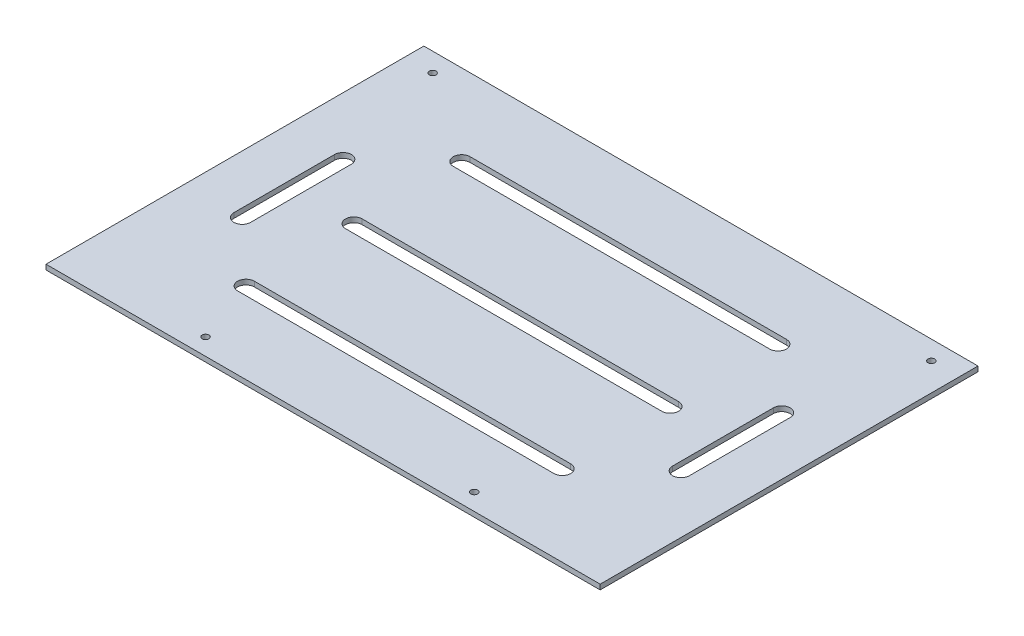
SolidWorks part; units mm, degrees
ref_plane "前视基准面" through (0, 0, 0) normal (0, 0, 1) x (1, 0, 0)
ref_plane "上视基准面" through (0, 0, 0) normal (0, 1, 0) x (1, 0, 0)
ref_plane "右视基准面" through (0, 0, 0) normal (1, 0, 0) x (0, 0, -1)
sketch "草图1" plane through (0, 0, 0) normal (0, 1, 0) x (1, 0, 0)
  line L1 (-145.5882, 128.3824) -> (184.4118, 128.3824)
  line L2 (-145.5882, 128.3824) -> (-145.5882, -96.6176)
  line L3 (-145.5882, -96.6176) -> (184.4118, -96.6176)
  line L4 (184.4118, 128.3824) -> (184.4118, -96.6176)
  dimension "D1" = 330
  dimension "D2" = 225
extrude "凸台-拉伸1" add sketch "草图1" along normal blind 3
sketch "草图2" plane through (0, 3, 0) normal (0, 1, 0) x (1, 0, 0)
  line L0 (-145.5882, 128.3824) -> (184.4118, -96.6176) construction
  line L1 (184.4118, 128.3824) -> (-145.5882, -96.6176) construction
sketch "草图3" plane through (0, 3, 0) normal (0, 1, 0) x (1, 0, 0)
  line L0 (-145.5882, 128.3824) -> (184.4118, -96.6176) construction
  line L1 (19.4118, 128.3824) -> (19.4118, -96.6176) construction
  line L2 (184.4118, 128.3824) -> (-145.5882, 128.3824) construction
  line L3 (-145.5882, -96.6176) -> (184.4118, -96.6176) construction
  line L5 (-145.5882, 15.8824) -> (184.4118, 15.8824) construction
  line L6 (-145.5882, 128.3824) -> (-145.5882, -96.6176) construction
  line L7 (184.4118, -96.6176) -> (184.4118, 128.3824) construction
  line L8 (19.4118, -86.6176) -> (50019.4118, -86.6176) construction
  circle A0 centre (-129.0637, 117.1156) radius 2
  circle A1 centre (167.8872, 117.1156) radius 2
  circle A2 centre (-60.5882, -86.6176) radius 2
  circle A3 centre (99.4118, -86.6176) radius 2
  dimension "D1" = 4
  dimension "D3" = 10
  dimension "D4" = 4
  dimension "D2" = 20
  dimension "D5" = 80
extrude "切除-拉伸1" cut sketch "草图3" against normal through all
sketch "草图4" plane through (0, 3, 0) normal (0, 1, 0) x (1, 0, 0)
  line L0 (-111.2352, 128.3824) -> (-111.2352, -96.6176) construction
  line L1 (184.4118, 128.3824) -> (-145.5882, 128.3824) construction
  line L2 (-145.5882, -96.6176) -> (184.4118, -96.6176) construction
  line L3 (19.4118, 128.3824) -> (19.4118, -96.6176) construction
  line L4 (150.0588, 128.3824) -> (150.0588, -96.6176) construction
  line L5 (-111.2352, -14.1176) -> (-111.2352, 45.8824) construction
  line L6 (-116.2352, -14.1176) -> (-116.2352, 45.8824)
  line L7 (-106.2352, -14.1176) -> (-106.2352, 45.8824)
  line L8 (150.0588, -14.1176) -> (150.0588, 45.8824) construction
  line L9 (155.0588, -14.1176) -> (155.0588, 45.8824)
  line L10 (145.0588, -14.1176) -> (145.0588, 45.8824)
  arc A0 (-116.2352, -14.1176) -> (-106.2352, -14.1176) centre (-111.2352, -14.1176) ccw
  arc A1 (-106.2352, 45.8824) -> (-116.2352, 45.8824) centre (-111.2352, 45.8824) ccw
  arc A2 (155.0588, -14.1176) -> (145.0588, -14.1176) centre (150.0588, -14.1176) cw
  arc A3 (145.0588, 45.8824) -> (155.0588, 45.8824) centre (150.0588, 45.8824) cw
  point P12 (-111.2352, 15.8824)
  point P19 (150.0588, 15.8824)
  dimension "D1" = 5
  dimension "D2" = 60
extrude "切除-拉伸2" cut sketch "草图4" against normal through all
sketch "草图5" plane through (0, 3, 0) normal (0, 1, 0) x (1, 0, 0)
  line L0 (-74.7746, 80.1003) -> (113.5981, 80.1003) construction
  line L1 (-145.5882, 128.3824) -> (184.4118, -96.6176) construction
  line L2 (184.4118, 128.3824) -> (-145.5882, -96.6176) construction
  line L3 (-74.7746, 85.1003) -> (113.5981, 85.1003)
  line L4 (-74.7746, 75.1003) -> (113.5981, 75.1003)
  line L5 (-145.5882, 15.8824) -> (184.4118, 15.8824) construction
  line L6 (-145.5882, 128.3824) -> (-145.5882, -96.6176) construction
  line L7 (184.4118, -96.6176) -> (184.4118, 128.3824) construction
  line L8 (-74.7746, -48.3356) -> (113.5981, -48.3356) construction
  line L9 (-74.7746, -53.3356) -> (113.5981, -53.3356)
  line L10 (-74.7746, -43.3356) -> (113.5981, -43.3356)
  arc A0 (-74.7746, 85.1003) -> (-74.7746, 75.1003) centre (-74.7746, 80.1003) ccw
  arc A1 (113.5981, 75.1003) -> (113.5981, 85.1003) centre (113.5981, 80.1003) ccw
  arc A2 (-74.7746, -53.3356) -> (-74.7746, -43.3356) centre (-74.7746, -48.3356) cw
  arc A3 (113.5981, -43.3356) -> (113.5981, -53.3356) centre (113.5981, -48.3356) cw
  point P6 (19.4118, 80.1003)
  point P11 (118.5981, 80.1003)
  point P19 (0, 0)
  point P21 (19.4118, -48.3356)
  dimension "D1" = 5
extrude "切除-拉伸3" cut sketch "草图5" against normal through all
sketch "草图6" plane through (0, 3, 0) normal (0, 1, 0) x (1, 0, 0)
  line L0 (-74.7732, 15.8824) -> (113.5968, 15.8824) construction
  line L1 (-145.5882, 128.3824) -> (184.4118, -96.6176) construction
  line L2 (-74.7732, 20.8824) -> (113.5968, 20.8824)
  line L3 (-74.7732, 10.8824) -> (113.5968, 10.8824)
  arc A0 (-74.7732, 20.8824) -> (-74.7732, 10.8824) centre (-74.7732, 15.8824) ccw
  arc A1 (113.5968, 10.8824) -> (113.5968, 20.8824) centre (113.5968, 15.8824) ccw
  point P4 (19.4118, 15.8824)
  dimension "D2" = 5
  dimension "D1" = 188.37
extrude "切除-拉伸4" cut sketch "草图6" against normal through all
